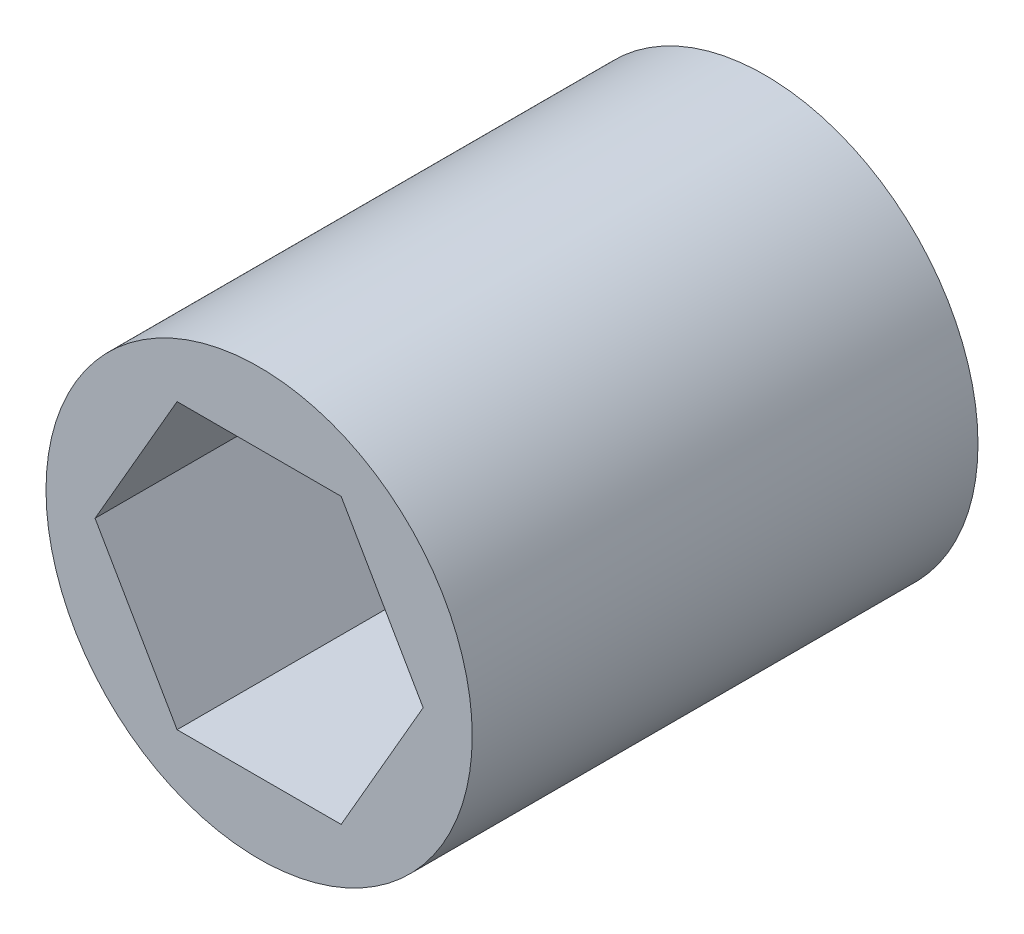
SolidWorks part; units mm, degrees
material "Nylon 101"
ref_plane "Front Plane" through (0, 0, 0) normal (0, 0, 1) x (1, 0, 0)
ref_plane "Top Plane" through (0, 0, 0) normal (0, 1, 0) x (1, 0, 0)
ref_plane "Right Plane" through (0, 0, 0) normal (1, 0, 0) x (0, 0, -1)
sketch "Sketch1" plane through (0, 0, 0) normal (0, 0, 1) x (1, 0, 0)
  line L1 (3.6662, 6.35) -> (-3.6662, 6.35)
  line L2 (-3.6662, 6.35) -> (-7.3323, 0)
  line L3 (-7.3323, 0) -> (-3.6662, -6.35)
  line L4 (-3.6662, -6.35) -> (3.6662, -6.35)
  line L5 (3.6662, -6.35) -> (7.3323, 0)
  line L6 (7.3323, 0) -> (3.6662, 6.35)
  circle A0 centre (0, 0) radius 6.35 construction
  circle A1 centre (0, 0) radius 9.525
  point P10 (0, 6.35)
  dimension "D1" = 19.05
  dimension "D2" = 12.7
extrude "Boss-Extrude1" add sketch "Sketch1" along normal blind 22.606
